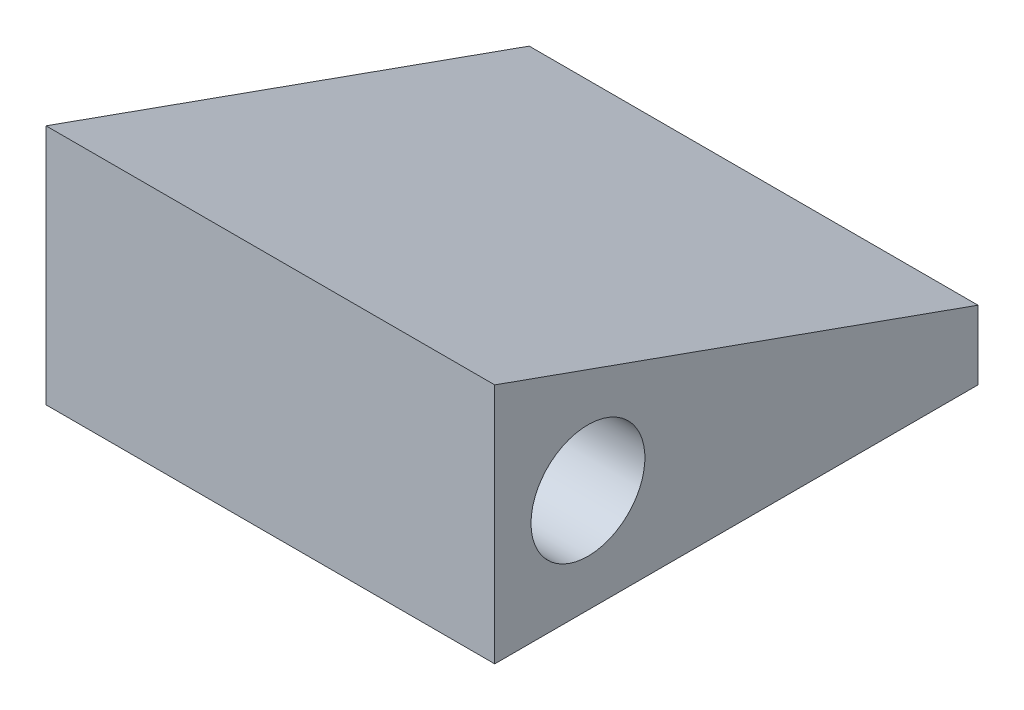
SolidWorks part; units mm, degrees
ref_plane "Front Plane" through (0, 0, 0) normal (0, 0, 1) x (1, 0, 0)
ref_plane "Top Plane" through (0, 0, 0) normal (0, 1, 0) x (1, 0, 0)
ref_plane "Right Plane" through (0, 0, 0) normal (1, 0, 0) x (0, 0, -1)
sketch "Sketch1" plane through (0, 0, 0) normal (0, 1, 0) x (1, 0, 0)
  line L1 (-6.5, 7) -> (6.5, 7)
  line L2 (-6.5, 7) -> (-6.5, -7)
  line L3 (-6.5, -7) -> (6.5, -7)
  line L4 (6.5, 7) -> (6.5, -7)
  line L5 (-6.5, 7) -> (6.5, -7) construction
  line L6 (-6.5, -7) -> (6.5, 7) construction
  point P0 (0, 0)
  dimension "D1" = 14
  dimension "D2" = 13
extrude "Boss-Extrude1" add sketch "Sketch1" along normal blind 2
sketch "Sketch2" plane through (6.5, 0, 0) normal (1, 0, 0) x (0, 0, -1)
  line L0 (-7, 2) -> (-7, 7)
  line L1 (-7, 7) -> (7, 2)
  line L2 (7, 2) -> (-7, 2)
  dimension "D1" = 5
extrude "Boss-Extrude2" add sketch "Sketch2" against normal blind 13
sketch "Sketch3" plane through (-6.5, 0, 0) normal (-1, 0, 0) x (0, 0, 1)
  line L0 (-7, 0) -> (7, 0) construction
  line L1 (7, 7) -> (7, 0) construction
  circle A0 centre (4.3, 3) radius 1.65
  dimension "D1" = 3.3
  dimension "D2" = 3
  dimension "D3" = 2.7
extrude "Cut-Extrude1" cut sketch "Sketch3" against normal blind 13
